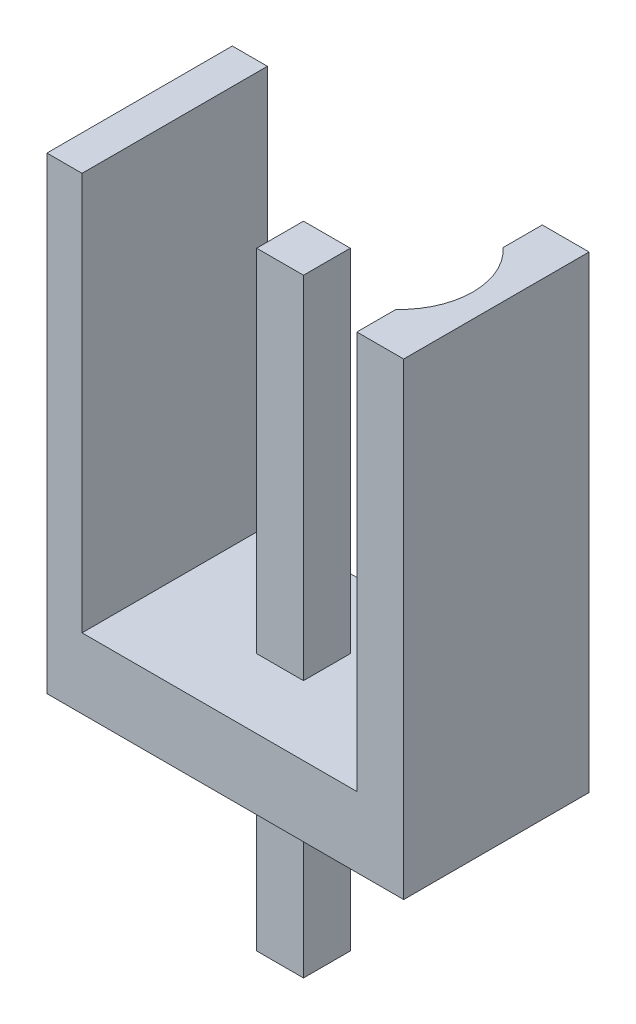
SolidWorks part; units mm, degrees
ref_plane "前视基准面" through (0, 0, 0) normal (0, 0, 1) x (1, 0, 0)
ref_plane "上视基准面" through (0, 0, 0) normal (0, 1, 0) x (1, 0, 0)
ref_plane "右视基准面" through (0, 0, 0) normal (1, 0, 0) x (0, 0, -1)
sketch "草图1" plane through (0, 0, 0) normal (0, 1, 0) x (1, 0, 0)
  line L0 (0, 11.3571) -> (0, -8.6742) construction
  line L1 (-3.81, 1.98) -> (3.81, 1.98)
  line L2 (-3.81, 1.98) -> (-3.81, -1.98)
  line L3 (-3.81, -1.98) -> (3.81, -1.98)
  line L4 (3.81, 1.98) -> (3.81, -1.98)
  line L5 (-11.8577, 0) -> (16.1453, 0) construction
  dimension "D1" = 7.62
  dimension "D2" = 3.96
extrude "拉伸1" add sketch "草图1" along normal blind 10
sketch "草图2" plane through (0, 10, 0) normal (0, 1, 0) x (-1, 0, 0)
  line L0 (-4.9146, 0) -> (4.5942, 0) construction
  line L1 (-1.7494, 0) -> (-4.2075, 0) construction
  line L2 (-2.81, 1.1448) -> (-2.81, 1.98)
  line L3 (-3.81, 1.98) -> (-3.81, -1.98) construction
  line L4 (-2.81, -1.1448) -> (-2.81, -1.98)
  line L5 (-3.31, 0) -> (-3.31, -3.9781) construction
  line L7 (3.06, -1.98) -> (3.06, 1.98)
  line L8 (-3.81, -1.98) -> (3.81, -1.98) construction
  line L9 (3.81, -1.98) -> (3.81, 1.98) construction
  line L10 (-2.81, 1.98) -> (3.06, 1.98)
  line L14 (-2.81, -1.98) -> (3.06, -1.98)
  arc A1 (-2.81, 1.1448) -> (-2.81, -1.1448) centre (-1.7494, 0) ccw
  point P16 (-2.81, 0)
  point P25 (3.06, 0)
  dimension "D1" = 1
  dimension "D2" = 1.5606
  dimension "D4" = 0.5
  dimension "D5" = 0.75
extrude "切除-拉伸1" cut sketch "草图2" against normal offset from surface (8.5 mm away) 1.5 up to face at (0, 0, 0)
sketch "草图3" plane through (0, 0, 0) normal (0, -1, 0) x (1, 0, 0)
  line L0 (4.5117, 0) -> (-4.6667, 0) construction
  line L1 (2.1187, 0) -> (-2.5308, 0) construction
  line L2 (0.19, 0.5) -> (-0.81, 0.5)
  line L3 (0.19, 0.5) -> (0.19, -0.5)
  line L4 (0.19, -0.5) -> (-0.81, -0.5)
  line L5 (-0.81, 0.5) -> (-0.81, -0.5)
  line L6 (-0.31, 3.5474) -> (-0.31, 0.8266) construction
  line L7 (-3.81, -1.98) -> (-3.81, 1.98) construction
  dimension "D1" = 1
  dimension "D2" = 1
  dimension "D4" = 3.5
extrude "拉伸2" add sketch "草图3" along normal blind 4 and the other way offset from surface (9 mm away) 1 other way up to face at (-3.435, 10, 0)
